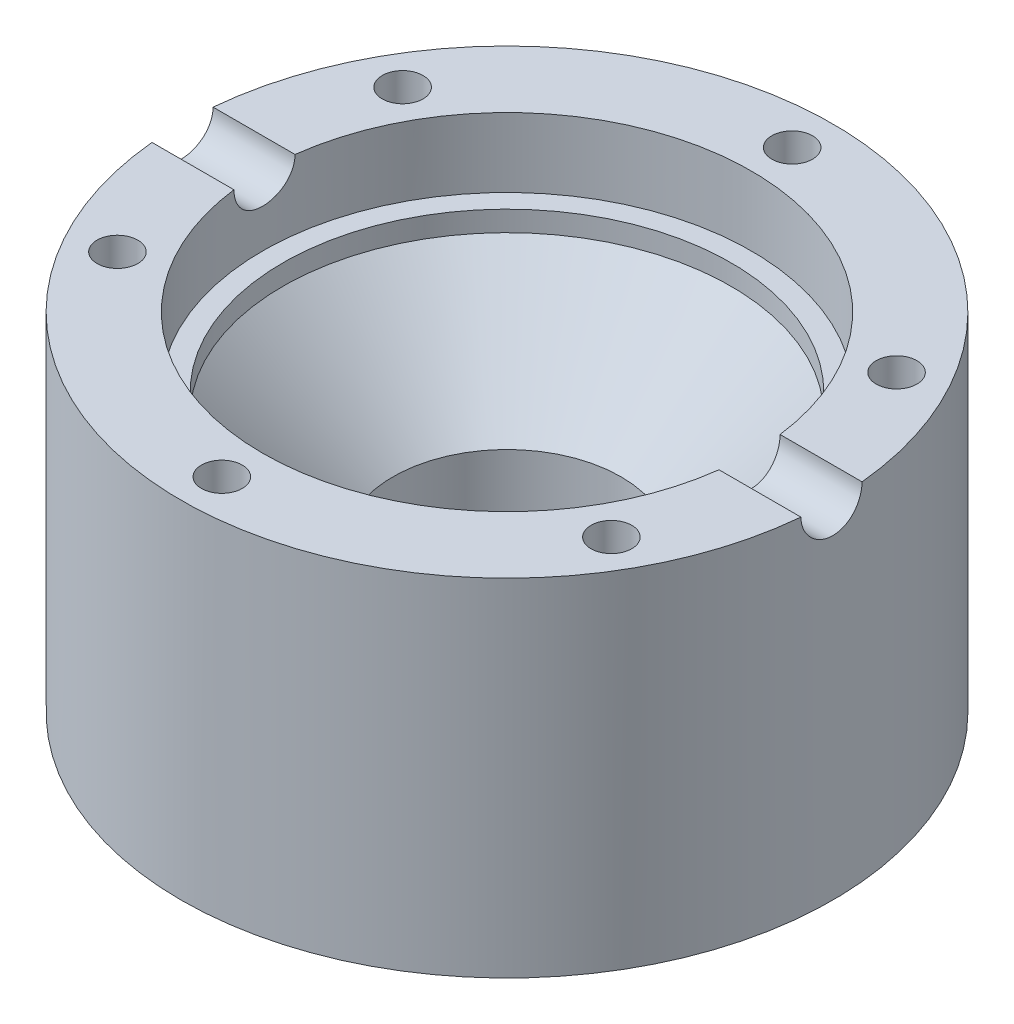
SolidWorks part; units mm, degrees
ref_plane "Front Plane" through (0, 0, 0) normal (0, 0, 1) x (1, 0, 0)
ref_plane "Top Plane" through (0, 0, 0) normal (0, 1, 0) x (1, 0, 0)
ref_plane "Right Plane" through (0, 0, 0) normal (1, 0, 0) x (0, 0, -1)
ref_axis "Centerline" through (0, 22.7835, 0) along (0, -1, 0)
sketch "Sketch1" plane through (0, 0, 0) normal (0, 1, 0) x (1, 0, 0)
  circle A0 centre (0, 0) radius 20.32
  dimension "D1" = 40.64
extrude "Boss-Extrude1" add sketch "Sketch1" along normal blind 21.59
sketch "Sketch2" plane through (0, 0, 0) normal (0, 0, 1) x (1, 0, 0)
  line L0 (0, 26.2246) -> (0, -7.0612) construction
  line L5 (20.32, 21.59) -> (-20.32, 21.59) construction
  line L6 (0, 21.59) -> (-15.24, 21.59)
  line L7 (0, 21.59) -> (0, 17.272)
  line L8 (0, 17.272) -> (-15.24, 17.272)
  line L9 (-15.24, 21.59) -> (-15.24, 17.272)
  line L10 (-20.32, 21.59) -> (-20.32, 0) construction
  dimension "D1" = 5.08
  dimension "D2" = 4.318
revolve "Cut-Revolve1" cut sketch "Sketch2" angle 360 about axis through (0, 22.7835, 0) along (0, -1, 0)
sketch "Sketch3" plane through (0, 0, 0) normal (0, 0, 1) x (1, 0, 0)
  line L0 (-20.32, 0) -> (20.32, 0) construction
  line L1 (-20.32, 14.732) -> (-15.24, 14.732)
  line L2 (-20.32, 14.732) -> (-20.32, 0)
  line L3 (-20.32, 0) -> (-15.24, 0)
  line L4 (-15.24, 14.732) -> (-15.24, 0)
  line L5 (20.32, 21.59) -> (-20.32, 21.59) construction
  line L6 (-20.32, 21.59) -> (-20.32, 0) construction
  dimension "D1" = 6.858
  dimension "D2" = 5.08
sketch "Sketch4" plane through (0, 21.59, 0) normal (0, 1, 0) x (1, 0, 0)
  line L0 (0, 29.0947) -> (0, -35.1526) construction
  circle A0 centre (0, 17.78) radius 1.27
  dimension "D1" = 2.54
  dimension "D2" = 17.78
extrude "Cut-Extrude1" cut sketch "Sketch4" against normal up to next
pattern_circular "CirPattern1" count 6 over 360 about axis through (0, 0, 0) along (0, 1, 0) of "Cut-Extrude1"
sketch "Sketch8" plane through (0, 0, 0) normal (0, 0, 1) x (1, 0, 0)
  line L0 (-4.699, 24.8968) -> (-4.699, 18.7411) construction
  line L1 (-15.24, 24.5608) -> (-15.24, -3.2139) construction
  line L2 (15.24, 17.272) -> (-15.24, 17.272) construction
  line L3 (-4.699, 17.272) -> (-13.97, 17.272)
  line L4 (-13.97, 16.002) -> (-4.699, 6.731)
  line L5 (-22.2629, 0) -> (17.7783, 0) construction
  line L6 (-4.699, 6.731) -> (-4.699, 17.272)
  line L7 (-4.699, 17.272) -> (-4.699, -4.4972) construction
  line L8 (-13.97, 17.272) -> (-13.97, 16.002)
  line L9 (-13.97, 16.002) -> (-15.24, 17.272) construction
  line L10 (-15.24, 17.272) -> (-13.97, 17.272) construction
  dimension "D1" = 4.699
  dimension "D2" = 15.24
  dimension "D3" = 45
  dimension "D4" = 1.27
revolve "Cut-Revolve4" cut sketch "Sketch8" angle 360 about axis through (0, 22.7835, 0) along (0, -1, 0)
ref_plane "Inlet Plane" through (20.32, 0, 0) normal (1, 0, 0) x (0, 0, -1)
sketch "Sketch9" plane through (20.32, 0, 0) normal (1, 0, 0) x (0, 0, -1)
  line L0 (0, 25.9244) -> (0, -6.8119) construction
  line L1 (20.32, 21.59) -> (-20.32, 21.59) construction
  circle A0 centre (0, 21.59) radius 1.905
  dimension "D1" = 3.81
extrude "Cut-Extrude3" cut sketch "Sketch9" against normal through all
sketch "Sketch10" plane through (0, 0, 0) normal (0, 1, 0) x (1, 0, 0)
  circle A0 centre (0, 0) radius 7.112
extrude "Cut-Extrude8" cut sketch "Sketch10" along a picked direction on the side of the normal blind 17.272 contours A0
sketch "Sketch11" plane through (0, 0, 0) normal (0, 1, 0) x (1, 0, 0)
  line L0 (0, 0) -> (15.3979, 8.89) construction
  line L1 (0, 0) -> (0, 17.78) construction
  dimension "D1" = 60
